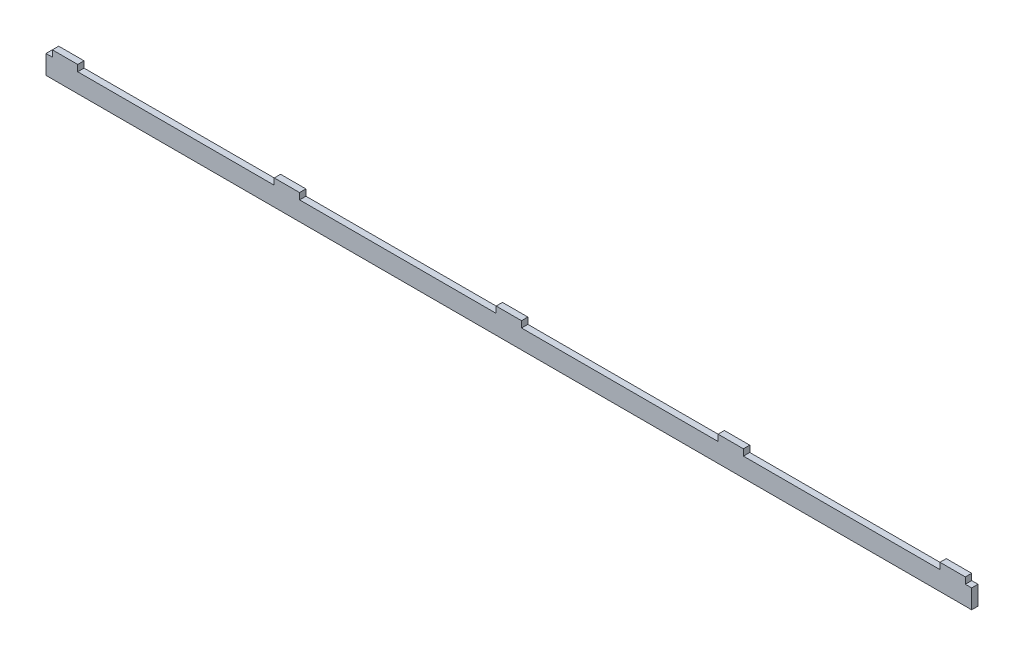
SolidWorks part; units mm, degrees
material "7075-T6 (SN)"
ref_plane "Front Plane" through (0, 0, 0) normal (0, 0, 1) x (1, 0, 0)
ref_plane "Top Plane" through (0, 0, 0) normal (0, 1, 0) x (1, 0, 0)
ref_plane "Right Plane" through (0, 0, 0) normal (1, 0, 0) x (0, 0, -1)
sketch "Sketch1" plane through (0, 0, 0) normal (0, 0, 1) x (1, 0, 0)
  line L0 (-115.8875, 0) -> (115.8875, 0)
  line L1 (115.8875, 0) -> (115.8875, 4.7625)
  line L2 (115.8875, 4.7625) -> (114.3, 4.7625)
  line L3 (114.3, 4.7625) -> (114.3, 6.35)
  line L4 (114.3, 6.35) -> (107.95, 6.35)
  line L5 (107.95, 6.35) -> (107.95, 4.7625)
  line L6 (107.95, 4.7625) -> (58.7375, 4.7625)
  line L7 (58.7375, 4.7625) -> (58.7375, 6.35)
  line L8 (58.7375, 6.35) -> (52.3875, 6.35)
  line L9 (52.3875, 6.35) -> (52.3875, 4.7625)
  line L10 (52.3875, 4.7625) -> (3.175, 4.7625)
  line L11 (3.175, 4.7625) -> (3.175, 6.35)
  line L12 (3.175, 6.35) -> (-3.175, 6.35)
  line L13 (-3.175, 6.35) -> (-3.175, 4.7625)
  line L14 (-3.175, 4.7625) -> (-52.3875, 4.7625)
  line L15 (-52.3875, 4.7625) -> (-52.3875, 6.35)
  line L16 (-52.3875, 6.35) -> (-58.7375, 6.35)
  line L17 (-58.7375, 6.35) -> (-58.7375, 4.7625)
  line L18 (-58.7375, 4.7625) -> (-107.95, 4.7625)
  line L19 (-107.95, 4.7625) -> (-107.95, 6.35)
  line L20 (-107.95, 6.35) -> (-114.3, 6.35)
  line L21 (-114.3, 6.35) -> (-114.3, 4.7625)
  line L22 (-114.3, 4.7625) -> (-115.8875, 4.7625)
  line L23 (-115.8875, 4.7625) -> (-115.8875, 0)
  point P7 (0, 6.35)
  dimension "D1" = 4.7625
  dimension "D2" = 1.5875
  dimension "D3" = 1.5875
  dimension "D4" = 6.35
  dimension "D5" = 6.35
  dimension "D6" = 231.775
extrude "Boss-Extrude1" add sketch "Sketch1" along normal mid plane 1.5875
